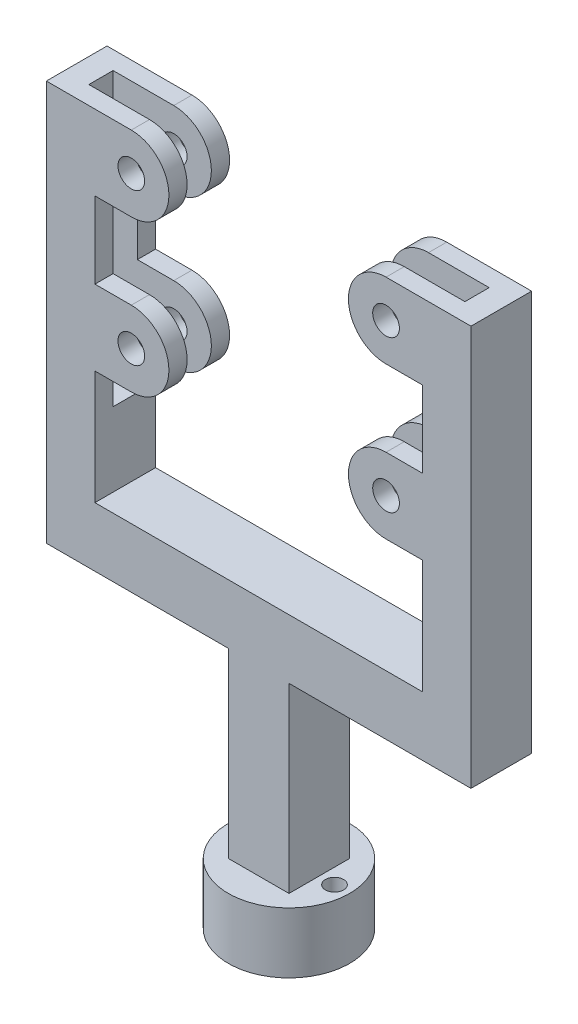
SolidWorks part; units mm, degrees
ref_plane "Ön Düzlem" through (0, 0, 0) normal (0, 0, 1) x (1, 0, 0)
ref_plane "Üst Düzlem" through (0, 0, 0) normal (0, 1, 0) x (1, 0, 0)
ref_plane "Sağ Düzlem" through (0, 0, 0) normal (1, 0, 0) x (0, 0, -1)
sketch "Sketch1" plane through (0, 0, 0) normal (0, 0, 1) x (1, 0, 0)
  line L23 (-10.5, 9.35) -> (-17.5, 9.35)
  line L24 (-10.5, 6.25) -> (10.5, 6.25) construction
  line L25 (-10.5, 6.25) -> (-10.5, -6.25) construction
  line L26 (-10.5, -6.25) -> (10.5, -6.25) construction
  line L27 (10.5, 6.25) -> (10.5, -6.25) construction
  line L28 (-10.5, 6.25) -> (10.5, -6.25) construction
  line L29 (-10.5, -6.25) -> (10.5, 6.25) construction
  line L30 (-17.5, 9.35) -> (-17.5, -23.65)
  line L32 (17.5, -23.65) -> (17.5, 9.35)
  line L33 (17.5, 9.35) -> (10.5, 9.35)
  line L34 (-10.5, -3.15) -> (-13.5, -3.15)
  line L35 (-13.5, -3.15) -> (-13.5, 3.15)
  line L36 (-13.5, 3.15) -> (-10.5, 3.15)
  line L37 (10.5, -3.15) -> (13.5, -3.15)
  line L38 (13.5, -3.15) -> (13.5, 3.15)
  line L39 (13.5, 3.15) -> (10.5, 3.15)
  line L40 (-10.5, -9.35) -> (-13.5, -9.35)
  line L41 (-13.5, -9.35) -> (-13.5, -18.75)
  line L42 (-13.5, -18.75) -> (13.5, -18.75)
  line L43 (13.5, -18.75) -> (13.5, -9.35)
  line L44 (13.5, -9.35) -> (10.5, -9.35)
  line L50 (-2.5, -23.65) -> (-2.5, -38.65)
  line L51 (-2.5, -38.65) -> (2.5, -38.65)
  line L52 (2.5, -38.65) -> (2.5, -23.65)
  line L53 (-17.5, -23.65) -> (-2.5, -23.65)
  line L54 (2.5, -23.65) -> (17.5, -23.65)
  circle A8 centre (-10.5, 6.25) radius 1.1
  circle A10 centre (10.5, 6.25) radius 1.1
  circle A11 centre (10.5, -6.25) radius 1.1
  circle A13 centre (-10.5, -6.25) radius 1.1
  arc A14 (-10.5, 3.15) -> (-10.5, 9.35) centre (-10.5, 6.25) ccw
  arc A15 (-10.5, -9.35) -> (-10.5, -3.15) centre (-10.5, -6.25) ccw
  arc A16 (10.5, -3.15) -> (10.5, -9.35) centre (10.5, -6.25) ccw
  arc A17 (10.5, 9.35) -> (10.5, 3.15) centre (10.5, 6.25) ccw
  circle A18 centre (-10.5, 6.25) radius 3.1 construction
  circle A19 centre (-10.5, -6.25) radius 3.1 construction
  circle A20 centre (10.5, -6.25) radius 3.1 construction
  circle A21 centre (10.5, 6.25) radius 3.1 construction
  point P0 (0, 0)
  dimension "D4" = 2
  dimension "D7" = 25
  dimension "D8" = 33
  dimension "D9" = 15
  dimension "D11" = 2.5
  dimension "D3" = 2.2
  dimension "D6" = 3
  dimension "D5" = 7
  dimension "D1" = 21
  dimension "D2" = 12.5
  dimension "D12" = 2.5
extrude "Boss-Extrude1" add sketch "Sketch1" along normal blind 5
sketch "Sketch2" plane through (0, 9.35, 0) normal (0, 1, 0) x (1, 0, 0)
  line L1 (-15.5, -1.5) -> (15.5, -1.5)
  line L2 (-15.5, -1.5) -> (-15.5, -3.5)
  line L3 (-15.5, -3.5) -> (15.5, -3.5)
  line L4 (15.5, -1.5) -> (15.5, -3.5)
  line L5 (-15.5, -1.5) -> (15.5, -3.5) construction
  line L6 (-15.5, -3.5) -> (15.5, -1.5) construction
  line L7 (-10.5, -5) -> (-10.5, 0) construction
  line L8 (10.5, -5) -> (10.5, 0) construction
  line L9 (13.5, 0) -> (-13.5, 0) construction
  point P0 (0, -2.5)
  dimension "D1" = 2
  dimension "D2" = 1.5
  dimension "D3" = 5
  dimension "D4" = 5
extrude "Cut-Extrude1" cut sketch "Sketch2" against normal blind 22
sketch "Sketch4" plane through (0, -38.65, 0) normal (0, -1, 0) x (1, 0, 0)
  circle A0 centre (0, 2.5) radius 5
  dimension "D1" = 10
extrude "Boss-Extrude2" add sketch "Sketch4" along normal blind 5
hole_wizard "Ø1.5mm Dowel Hole1" positions "3DSketch1" profile "Sketch5" hole size "Ø1.5" standard "ANSI Metric"
sketch3d "3DSketch1"
  line L0 (-2.5, -38.65, 5) -> (-2.5, -38.65, 0) construction
  line L1 (2.5, -38.65, 5) -> (2.5, -38.65, 0) construction
  line L2 (-2.5, -38.65, 5) -> (2.5, -38.65, 5) construction
  point P0 (3.75, -38.65, 2.5)
  point P2 (-3.75, -38.65, 2.5)
  dimension "D1" = 1.25
  dimension "D2" = 1.25
  dimension "D3" = 2.5
  dimension "D4" = 2.5
sketch "Sketch5" plane through (3.75, -38.65, 2.5) normal (1, 0, 0) x (0, 0, 1)
  line L0 (0, 0) -> (0, 5)
  line L1 (0, 5) -> (0.75, 5)
  line L2 (0.75, 5) -> (0.75, 0)
  line L5 (0.75, 0) -> (0, 0)
  line L11 (0, -6.35) -> (0, 107.95) construction
  dimension "Thru Hole Dia." = 1.5
  dimension "Thru Hole Depth" = 5
